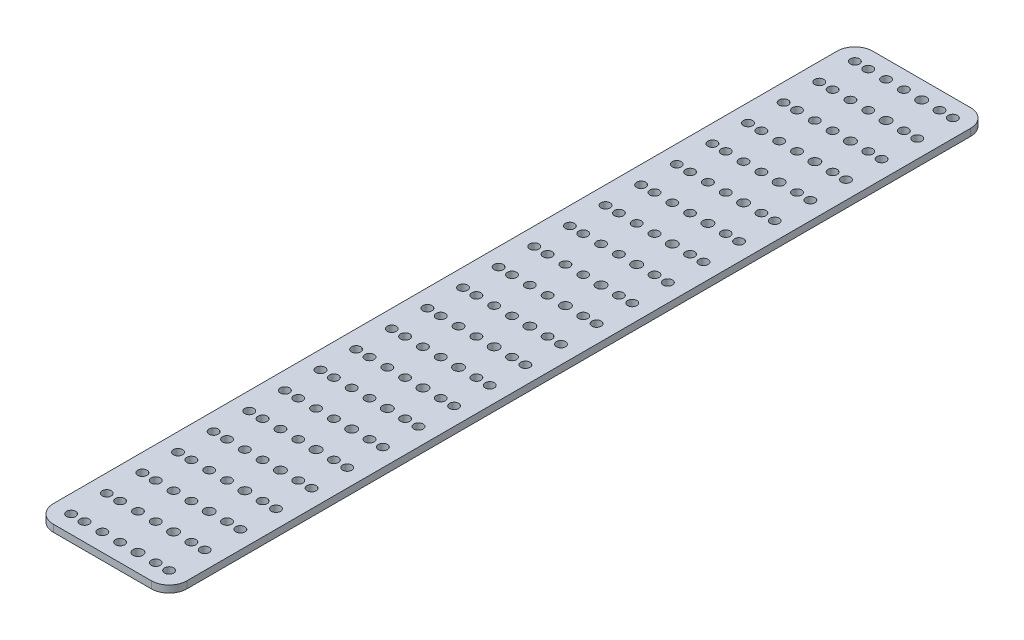
SolidWorks part; units mm, degrees
ref_plane "Front Plane" through (0, 0, 0) normal (0, 0, 1) x (1, 0, 0)
ref_plane "Top Plane" through (0, 0, 0) normal (0, 1, 0) x (1, 0, 0)
ref_plane "Right Plane" through (0, 0, 0) normal (1, 0, 0) x (0, 0, -1)
ref_plane "Plane1" through (0, 0, 0) normal (0, -1, 0) x (1, 0, 0)
sketch "Sketch1" plane through (0, 0, 0) normal (0, -1, 0) x (1, 0, 0)
  line L0 (-22, -184) -> (22, -184)
  line L1 (30, -176) -> (30, 176)
  line L2 (22, 184) -> (-22, 184)
  line L3 (-30, 176) -> (-30, -176)
  circle A0 centre (8, 176) radius 2.2188
  circle A1 centre (-8, 176) radius 2.05
  circle A2 centre (16, 176) radius 2.05
  circle A3 centre (22, 176) radius 2.05
  circle A4 centre (0, 176) radius 2.05
  circle A5 centre (-16, 176) radius 2.05
  circle A6 centre (-22, 176) radius 2.05
  circle A7 centre (8, 160) radius 2.2188
  circle A8 centre (-8, 160) radius 2.05
  circle A9 centre (16, 160) radius 2.05
  circle A10 centre (22, 160) radius 2.05
  circle A11 centre (0, 160) radius 2.05
  circle A12 centre (-16, 160) radius 2.05
  circle A13 centre (-22, 160) radius 2.05
  circle A14 centre (8, 144) radius 2.2188
  circle A15 centre (-8, 144) radius 2.05
  circle A16 centre (16, 144) radius 2.05
  circle A17 centre (22, 144) radius 2.05
  circle A18 centre (0, 144) radius 2.05
  circle A19 centre (-16, 144) radius 2.05
  circle A20 centre (-22, 144) radius 2.05
  circle A21 centre (8, 128) radius 2.2188
  circle A22 centre (-8, 128) radius 2.05
  circle A23 centre (16, 128) radius 2.05
  circle A24 centre (22, 128) radius 2.05
  circle A25 centre (0, 128) radius 2.05
  circle A26 centre (-16, 128) radius 2.05
  circle A27 centre (-22, 128) radius 2.05
  circle A28 centre (8, 112) radius 2.2188
  circle A29 centre (-8, 112) radius 2.05
  circle A30 centre (16, 112) radius 2.05
  circle A31 centre (22, 112) radius 2.05
  circle A32 centre (0, 112) radius 2.05
  circle A33 centre (-16, 112) radius 2.05
  circle A34 centre (-22, 112) radius 2.05
  circle A35 centre (8, 96) radius 2.2188
  circle A36 centre (-8, 96) radius 2.05
  circle A37 centre (16, 96) radius 2.05
  circle A38 centre (22, 96) radius 2.05
  circle A39 centre (0, 96) radius 2.05
  circle A40 centre (-16, 96) radius 2.05
  circle A41 centre (-22, 96) radius 2.05
  circle A42 centre (8, 80) radius 2.2188
  circle A43 centre (-8, 80) radius 2.05
  circle A44 centre (16, 80) radius 2.05
  circle A45 centre (22, 80) radius 2.05
  circle A46 centre (0, 80) radius 2.05
  circle A47 centre (-16, 80) radius 2.05
  circle A48 centre (-22, 80) radius 2.05
  circle A49 centre (8, 64) radius 2.2188
  circle A50 centre (-8, 64) radius 2.05
  circle A51 centre (16, 64) radius 2.05
  circle A52 centre (22, 64) radius 2.05
  circle A53 centre (0, 64) radius 2.05
  circle A54 centre (-16, 64) radius 2.05
  circle A55 centre (-22, 64) radius 2.05
  circle A56 centre (8, 48) radius 2.2188
  circle A57 centre (-8, 48) radius 2.05
  circle A58 centre (16, 48) radius 2.05
  circle A59 centre (22, 48) radius 2.05
  circle A60 centre (0, 48) radius 2.05
  circle A61 centre (-16, 48) radius 2.05
  circle A62 centre (-22, 48) radius 2.05
  circle A63 centre (8, 32) radius 2.2188
  circle A64 centre (-8, 32) radius 2.05
  circle A65 centre (16, 32) radius 2.05
  circle A66 centre (22, 32) radius 2.05
  circle A67 centre (0, 32) radius 2.05
  circle A68 centre (-16, 32) radius 2.05
  circle A69 centre (-22, 32) radius 2.05
  circle A70 centre (8, 16) radius 2.2188
  circle A71 centre (-8, 16) radius 2.05
  circle A72 centre (16, 16) radius 2.05
  circle A73 centre (22, 16) radius 2.05
  circle A74 centre (0, 16) radius 2.05
  circle A75 centre (-16, 16) radius 2.05
  circle A76 centre (-22, 16) radius 2.05
  circle A77 centre (8, 0) radius 2.2188
  circle A78 centre (-8, 0) radius 2.05
  circle A79 centre (16, 0) radius 2.05
  circle A80 centre (22, 0) radius 2.05
  circle A81 centre (0, 0) radius 2.05
  circle A82 centre (-16, 0) radius 2.05
  circle A83 centre (-22, 0) radius 2.05
  circle A84 centre (8, -16) radius 2.2188
  circle A85 centre (-8, -16) radius 2.05
  circle A86 centre (16, -16) radius 2.05
  circle A87 centre (22, -16) radius 2.05
  circle A88 centre (0, -16) radius 2.05
  circle A89 centre (-16, -16) radius 2.05
  circle A90 centre (-22, -16) radius 2.05
  circle A91 centre (8, -32) radius 2.2188
  circle A92 centre (-8, -32) radius 2.05
  circle A93 centre (16, -32) radius 2.05
  circle A94 centre (22, -32) radius 2.05
  circle A95 centre (0, -32) radius 2.05
  circle A96 centre (-16, -32) radius 2.05
  circle A97 centre (-22, -32) radius 2.05
  circle A98 centre (8, -48) radius 2.2188
  circle A99 centre (-8, -48) radius 2.05
  circle A100 centre (16, -48) radius 2.05
  circle A101 centre (22, -48) radius 2.05
  circle A102 centre (0, -48) radius 2.05
  circle A103 centre (-16, -48) radius 2.05
  circle A104 centre (-22, -48) radius 2.05
  circle A105 centre (8, -64) radius 2.2188
  circle A106 centre (-8, -64) radius 2.05
  circle A107 centre (16, -64) radius 2.05
  circle A108 centre (22, -64) radius 2.05
  circle A109 centre (0, -64) radius 2.05
  circle A110 centre (-16, -64) radius 2.05
  circle A111 centre (-22, -64) radius 2.05
  circle A112 centre (8, -80) radius 2.2188
  circle A113 centre (-8, -80) radius 2.05
  circle A114 centre (16, -80) radius 2.05
  circle A115 centre (22, -80) radius 2.05
  circle A116 centre (0, -80) radius 2.05
  circle A117 centre (-16, -80) radius 2.05
  circle A118 centre (-22, -80) radius 2.05
  circle A119 centre (8, -96) radius 2.2188
  circle A120 centre (-8, -96) radius 2.05
  circle A121 centre (16, -96) radius 2.05
  circle A122 centre (22, -96) radius 2.05
  circle A123 centre (0, -96) radius 2.05
  circle A124 centre (-16, -96) radius 2.05
  circle A125 centre (-22, -96) radius 2.05
  circle A126 centre (8, -112) radius 2.2188
  circle A127 centre (-8, -112) radius 2.05
  circle A128 centre (16, -112) radius 2.05
  circle A129 centre (22, -112) radius 2.05
  circle A130 centre (0, -112) radius 2.05
  circle A131 centre (-16, -112) radius 2.05
  circle A132 centre (-22, -112) radius 2.05
  circle A133 centre (8, -128) radius 2.2188
  circle A134 centre (-8, -128) radius 2.05
  circle A135 centre (16, -128) radius 2.05
  circle A136 centre (22, -128) radius 2.05
  circle A137 centre (0, -128) radius 2.05
  circle A138 centre (-16, -128) radius 2.05
  circle A139 centre (-22, -128) radius 2.05
  circle A140 centre (8, -144) radius 2.2188
  circle A141 centre (-8, -144) radius 2.05
  circle A142 centre (16, -144) radius 2.05
  circle A143 centre (22, -144) radius 2.05
  circle A144 centre (0, -144) radius 2.05
  circle A145 centre (-16, -144) radius 2.05
  circle A146 centre (-22, -144) radius 2.05
  circle A147 centre (8, -160) radius 2.2188
  circle A148 centre (-8, -160) radius 2.05
  circle A149 centre (16, -160) radius 2.05
  circle A150 centre (22, -160) radius 2.05
  circle A151 centre (0, -160) radius 2.05
  circle A152 centre (-16, -160) radius 2.05
  circle A153 centre (-22, -160) radius 2.05
  circle A154 centre (8, -176) radius 2.2188
  circle A155 centre (-8, -176) radius 2.05
  circle A156 centre (16, -176) radius 2.05
  circle A157 centre (22, -176) radius 2.05
  circle A158 centre (0, -176) radius 2.05
  circle A159 centre (-16, -176) radius 2.05
  circle A160 centre (-22, -176) radius 2.05
  arc A161 (22, -184) -> (30, -176) centre (22, -176) ccw
  arc A162 (30, 176) -> (22, 184) centre (22, 176) ccw
  arc A163 (-22, 184) -> (-30, 176) centre (-22, 176) ccw
  arc A164 (-30, -176) -> (-22, -184) centre (-22, -176) ccw
extrude "Boss-Extrude1" add sketch "Sketch1" against normal blind 3.175
